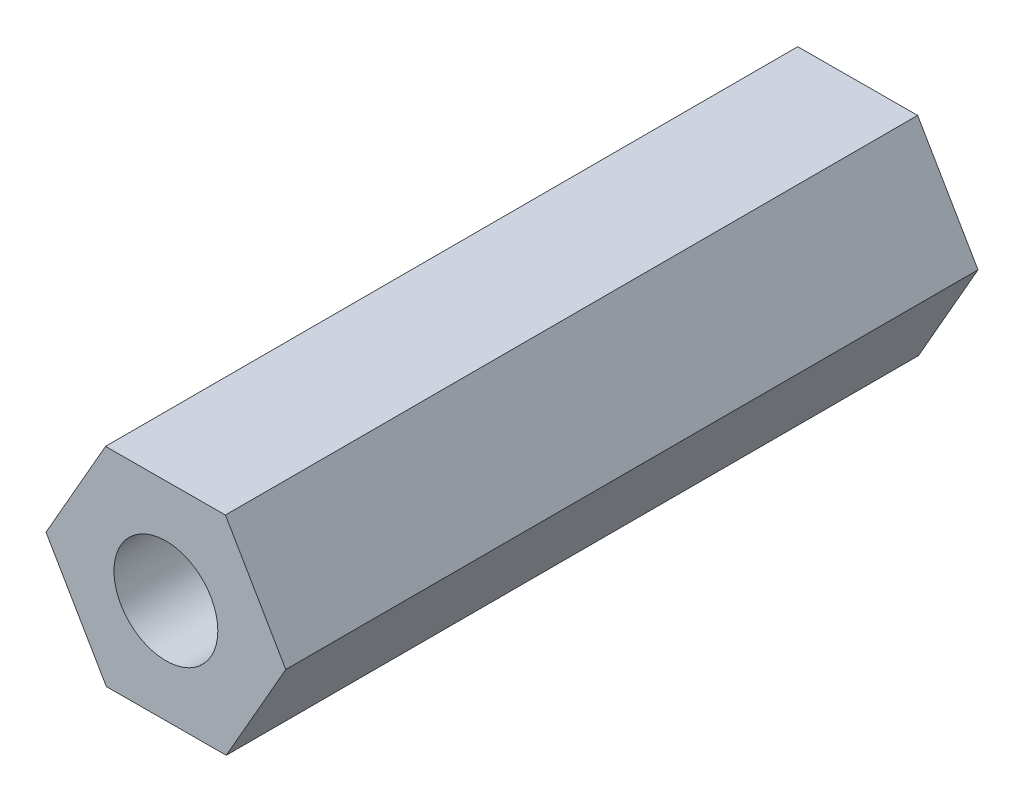
SolidWorks part; units mm, degrees
ref_plane "Front Plane" through (0, 0, 0) normal (0, 0, 1) x (1, 0, 0)
ref_plane "Top Plane" through (0, 0, 0) normal (0, 1, 0) x (1, 0, 0)
ref_plane "Right Plane" through (0, 0, 0) normal (1, 0, 0) x (0, 0, -1)
sketch "Sketch1" plane through (0, 0, 0) normal (0, 0, 1) x (1, 0, 0)
  line L1 (1.7201, 3.0069) -> (-1.744, 2.9931)
  line L2 (-1.744, 2.9931) -> (-3.4641, -0.0138)
  line L3 (-3.4641, -0.0138) -> (-1.7201, -3.0069)
  line L4 (-1.7201, -3.0069) -> (1.744, -2.9931)
  line L5 (1.744, -2.9931) -> (3.4641, 0.0138)
  line L6 (3.4641, 0.0138) -> (1.7201, 3.0069)
  circle A0 centre (0, 0) radius 1.5
  circle A2 centre (0, 0) radius 3 construction
  dimension "D1" = 3
extrude "Boss-Extrude1" add sketch "Sketch1" along normal blind 20
